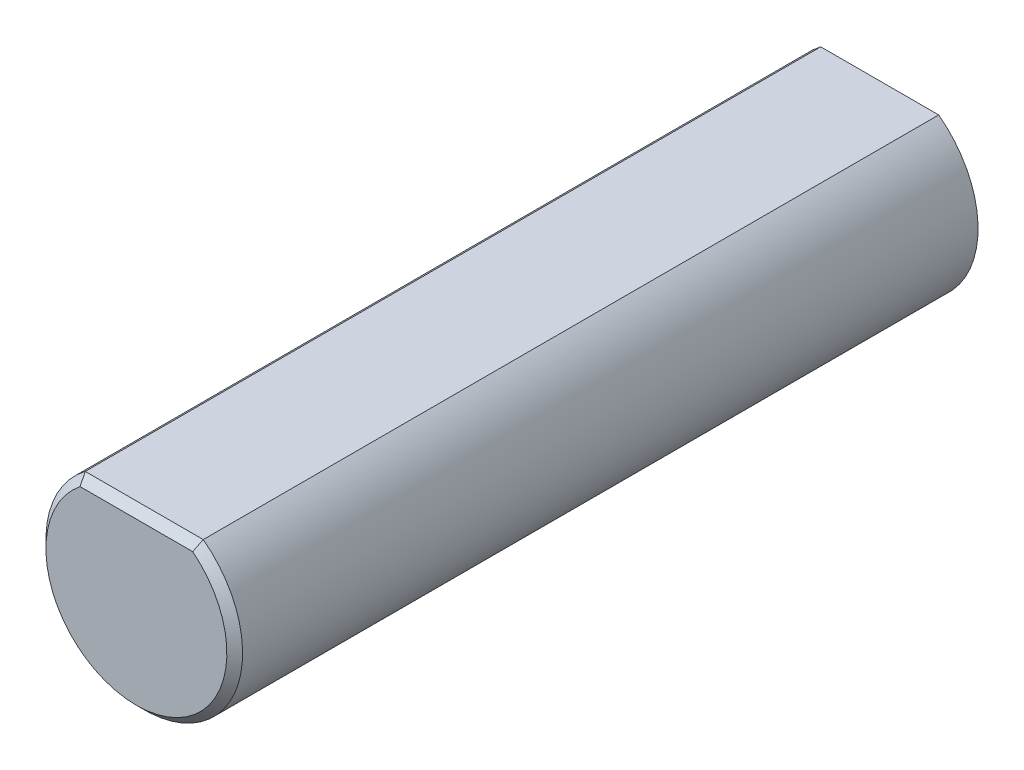
SolidWorks part; units mm, degrees
ref_plane "Front Plane" through (0, 0, 0) normal (0, 0, 1) x (1, 0, 0)
ref_plane "Top Plane" through (0, 0, 0) normal (0, 1, 0) x (1, 0, 0)
ref_plane "Right Plane" through (0, 0, 0) normal (1, 0, 0) x (0, 0, -1)
sketch "Sketch1" plane through (0, 0, 0) normal (0, 0, 1) x (1, 0, 0)
  line L1 (1.905, 2.54) -> (-1.905, 2.54)
  arc A0 (-1.905, 2.54) -> (1.905, 2.54) centre (0, 0) ccw
  dimension "D1" = 6.35
  dimension "D2" = 5.715
extrude "Boss-Extrude1" add sketch "Sketch1" along normal mid plane 24
chamfer "Chamfer1" distance 0.254 angle 45 2 edges at (0, 2.54, 12) (0, -3.175, 12)
